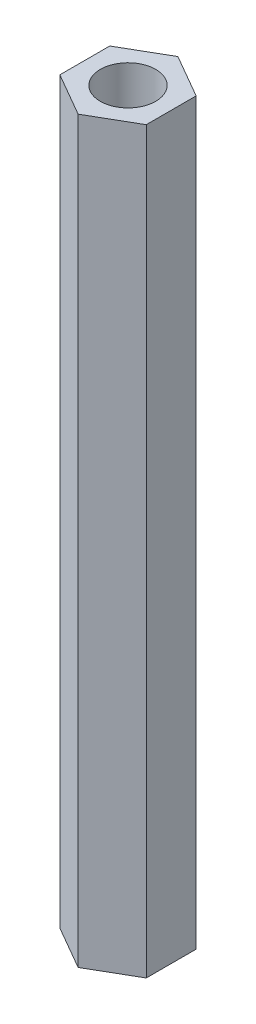
SolidWorks part; units mm, degrees
ref_plane "前视基准面" through (0, 0, 0) normal (0, 0, 1) x (1, 0, 0)
ref_plane "上视基准面" through (0, 0, 0) normal (0, 1, 0) x (1, 0, 0)
ref_plane "右视基准面" through (0, 0, 0) normal (1, 0, 0) x (0, 0, -1)
sketch "草图1" plane through (0, 0, 0) normal (0, 1, 0) x (1, 0, 0)
  circle A0 centre (0, 0) radius 1.5
  circle A1 centre (0, 0) radius 2.7
extrude "凸台-拉伸1" add sketch "草图1" along normal blind 40
sketch "草图2" plane through (0, 40, 0) normal (0, 1, 0) x (1, 0, 0)
  line L1 (0, 2.7) -> (-2.3383, 1.35)
  line L2 (-2.3383, 1.35) -> (-2.3383, -1.35)
  line L3 (-2.3383, -1.35) -> (0, -2.7)
  line L4 (0, -2.7) -> (2.3383, -1.35)
  line L5 (2.3383, -1.35) -> (2.3383, 1.35)
  line L6 (2.3383, 1.35) -> (0, 2.7)
  circle A0 centre (0, 0) radius 2.7
  circle A1 centre (0, 0) radius 2.3383 construction
  circle M1 centre (0, 0) radius 2.7
extrude "切除-拉伸1" cut sketch "草图2" against normal blind 40 contours L1 M1 | L2 M1 | L3 M1 | L4 M1 | L5 M1 | L6 M1
